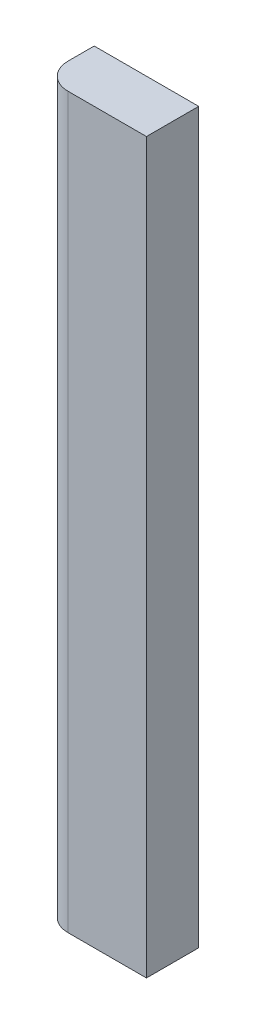
SolidWorks part; units mm, degrees
ref_plane "Front Plane" through (0, 0, 0) normal (0, 0, 1) x (1, 0, 0)
ref_plane "Top Plane" through (0, 0, 0) normal (0, 1, 0) x (1, 0, 0)
ref_plane "Right Plane" through (0, 0, 0) normal (1, 0, 0) x (0, 0, -1)
sketch "Sketch1" plane through (0, 0, 0) normal (0, 0, 1) x (1, 0, 0)
  line L1 (-17.2695, 674.898) -> (84.3305, 674.898)
  line L2 (-17.2695, 674.898) -> (-17.2695, -33.508)
  line L3 (-17.2695, -33.508) -> (84.3305, -33.508)
  line L4 (84.3305, 674.898) -> (84.3305, -33.508)
extrude "Boss-Extrude1" add sketch "Sketch1" along normal blind 50.8 contours L2 L1 L4 L3
fillet "Fillet1" radius 25.4 1 edges at (-17.2695, 320.695, 50.8)
